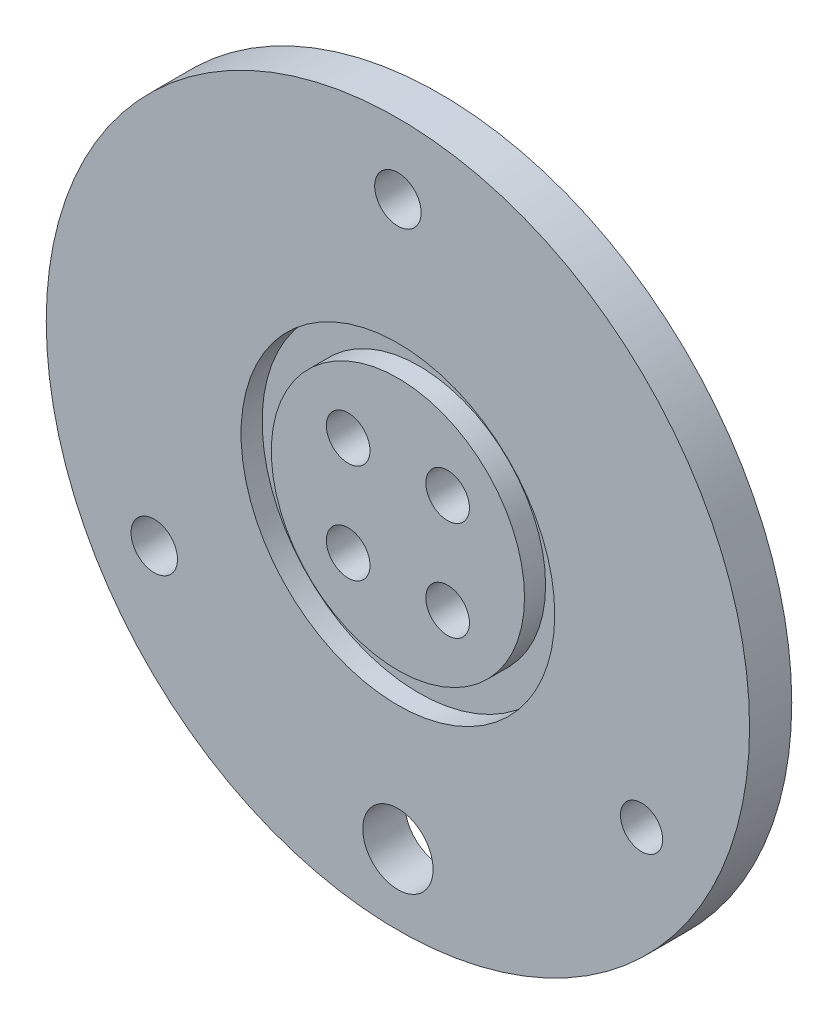
SolidWorks part; units mm, degrees
material "A-玻璃纤维"
ref_plane "前视基准面" through (0, 0, 0) normal (0, 0, 1) x (1, 0, 0)
ref_plane "上视基准面" through (0, 0, 0) normal (0, 1, 0) x (1, 0, 0)
ref_plane "右视基准面" through (0, 0, 0) normal (1, 0, 0) x (0, 0, -1)
sketch "草图1" plane through (0, 0, 0) normal (0, 0, 1) x (1, 0, 0)
  circle A0 centre (0, 0) radius 25
  circle B0 centre (0, 0) radius 11.05
  circle B1 centre (17.3205, -10) radius 1.5
  circle B2 centre (-17.3205, -10) radius 1.65
  circle B3 centre (0, 20) radius 1.65
  circle B4 centre (0, -20) radius 2.5
  circle B5 centre (0, 0) radius 20 construction
  dimension "D1" = 5
sketch_block_instance "6020电机安装孔-1"
sketch_block "6020电机安装孔"
sketch_block_instance "6020转子-1"
sketch_block "6020转子" parameters "D1"=22.1, "D2"=3, "D3"=5
extrude "凸台-拉伸1" add sketch "草图1" along normal blind 3 contours B0 | A0 B4 B3 B2 B1 B0
sketch "草图2" plane through (0, 0, 3) normal (0, 0, 1) x (1, 0, 0)
  circle A0 centre (0, 0) radius 11.15
  circle A1 centre (0, 0) radius 9
  dimension "D1" = 22.3
  dimension "D2" = 18
extrude "切除-拉伸1" cut sketch "草图2" against normal blind 1.5
sketch "草图4" plane through (0, 0, 3) normal (0, 0, 1) x (1, 0, 0)
  line L1 (-3.5355, 3.5355) -> (3.5355, 3.5355) construction
  line L2 (-3.5355, 3.5355) -> (-3.5355, -3.5355) construction
  line L3 (-3.5355, -3.5355) -> (3.5355, -3.5355) construction
  line L4 (3.5355, 3.5355) -> (3.5355, -3.5355) construction
  line L5 (0, -3.5355) -> (0, 3.5355) construction
  line L6 (-3.5355, 0) -> (3.5355, 0) construction
  circle A0 centre (-3.5355, 3.5355) radius 1.55
  circle A1 centre (3.5355, 3.5355) radius 1.55
  circle A2 centre (3.5355, -3.5355) radius 1.55
  circle A3 centre (-3.5355, -3.5355) radius 1.55
  circle A4 centre (0, 0) radius 5 construction
  point P96 (0, 0)
  dimension "D2" = 3.1
  dimension "D1" = 10
extrude "切除-拉伸2" cut sketch "草图4" against normal through all
